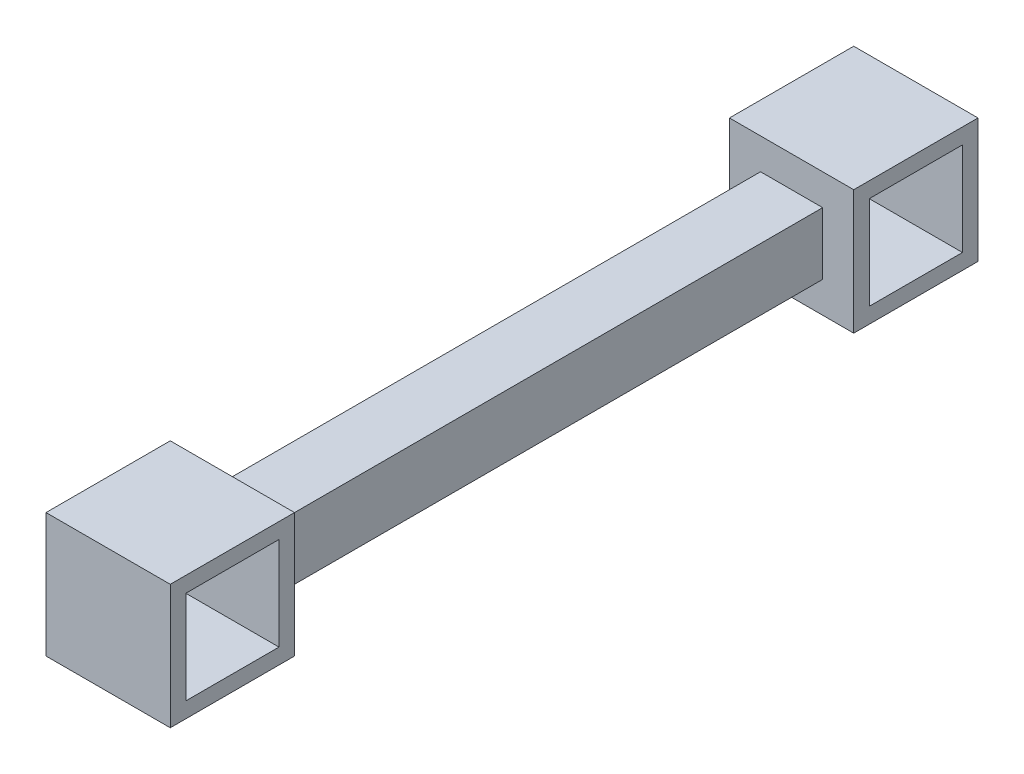
SolidWorks part; units mm, degrees
ref_plane "Front Plane" through (0, 0, 0) normal (0, 0, 1) x (1, 0, 0)
ref_plane "Top Plane" through (0, 0, 0) normal (0, 1, 0) x (1, 0, 0)
ref_plane "Right Plane" through (0, 0, 0) normal (1, 0, 0) x (0, 0, -1)
sketch "Sketch1" plane through (0, 0, 0) normal (0, 0, 1) x (1, 0, 0)
  line L1 (20, 20) -> (-20, 20)
  line L2 (20, 20) -> (20, -20)
  line L3 (20, -20) -> (-20, -20)
  line L4 (-20, 20) -> (-20, -20)
  line L5 (20, 20) -> (-20, -20) construction
  line L6 (20, -20) -> (-20, 20) construction
  point P0 (0, 0)
  dimension "D1" = 40
  dimension "D2" = 40
extrude "Boss-Extrude1" add sketch "Sketch1" along normal blind 260
ref_plane "Plane1" through (0, 0, 220) normal (0, 0, 1) x (1, 0, 0)
sketch "Sketch3" plane through (0, 0, 220) normal (0, 0, 1) x (1, 0, 0)
  line L0 (-20, -20) -> (20, -20) construction
  line L1 (20, -20) -> (20, 20) construction
  line L2 (-20, 20) -> (-20, -20) construction
  line L3 (20, 20) -> (-20, 20) construction
  line L4 (-20, -20) -> (20, -20)
  line L5 (20, -20) -> (20, 20)
  line L6 (-20, 20) -> (-20, -20)
  line L7 (20, 20) -> (-20, 20)
  line L8 (-10, 10) -> (-10, -10)
  line L9 (-10, -10) -> (10, -10)
  line L10 (10, -10) -> (10, 10)
  line L11 (10, 10) -> (-10, 10)
  dimension "D1" = 10
extrude "Cut-Extrude1" cut sketch "Sketch3" against normal blind 180
sketch "Sketch4" plane through (-20, 0, 0) normal (-1, 0, 0) x (0, 0, 1)
  line L0 (40, 20) -> (0, 20) construction
  line L2 (0, 20) -> (0, -20) construction
  line L4 (130, 10) -> (130, -10) construction
  line L6 (40, 10) -> (220, 10) construction
  line L7 (35, -15) -> (5, -15)
  line L8 (35, -15) -> (35, 15)
  line L9 (35, 15) -> (5, 15)
  line L10 (5, -15) -> (5, 15)
  line L11 (35, -15) -> (5, 15) construction
  line L12 (35, 15) -> (5, -15) construction
  line L13 (40, -10) -> (220, -10) construction
  line L14 (225, -15) -> (225, 15)
  line L15 (225, -15) -> (255, -15)
  line L16 (255, -15) -> (255, 15)
  line L17 (225, 15) -> (255, 15)
  point P5 (20, 0)
  dimension "D1" = 30
  dimension "D2" = 30
  dimension "D3" = 5
  dimension "D4" = 5
extrude "Cut-Extrude2" cut sketch "Sketch4" against normal through all
